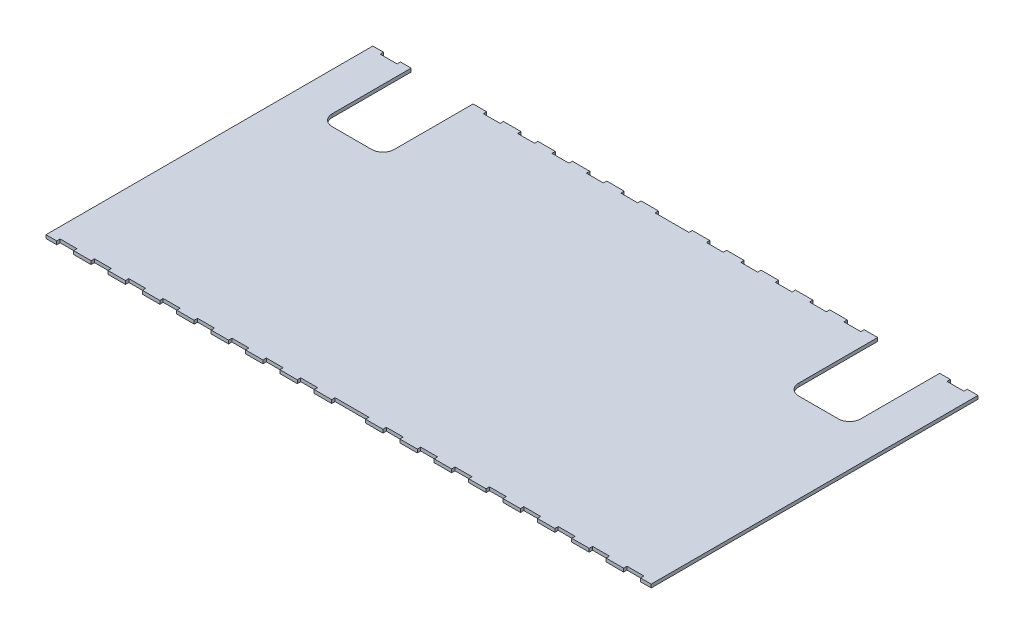
SolidWorks part; units mm, degrees
ref_plane "Front Plane" through (0, 0, 0) normal (0, 0, 1) x (1, 0, 0)
ref_plane "Top Plane" through (0, 0, 0) normal (0, 1, 0) x (1, 0, 0)
ref_plane "Right Plane" through (0, 0, 0) normal (1, 0, 0) x (0, 0, -1)
sketch "Sketch1" plane through (0, 0, 0) normal (0, 1, 0) x (1, 0, 0)
  line L1 (-268.5, 145) -> (268.5, 145)
  line L2 (-268.5, 145) -> (-268.5, -145)
  line L3 (-268.5, -145) -> (268.5, -145)
  line L4 (268.5, 145) -> (268.5, -145)
  line L5 (-268.5, 145) -> (268.5, -145) construction
  line L6 (-268.5, -145) -> (268.5, 145) construction
  line L7 (234.5, 145) -> (179.5, 145)
  line L8 (234.5, 145) -> (234.5, 65)
  line L9 (234.5, 65) -> (179.5, 65)
  line L10 (179.5, 145) -> (179.5, 65)
  line L15 (0, 145) -> (0, -145) construction
  line L16 (-179.5, 145) -> (-179.5, 65)
  line L17 (-234.5, 65) -> (-179.5, 65)
  line L18 (-234.5, 145) -> (-234.5, 65)
  line L19 (-234.5, 145) -> (-179.5, 145)
  point P0 (0, 0)
  dimension "D1" = 537
  dimension "D2" = 290
  dimension "D3" = 34
  dimension "D4" = 80
  dimension "D5" = 55
extrude "Boss-Extrude1" add sketch "Sketch1" along normal blind 3 contours L18 L1 L2 L3 L4 L8 L9 L10 L16 L17
fillet "Fillet1" radius 10 4 edges at (179.5, 1.5, -65) (234.5, 1.5, -65) (-179.5, 1.5, -65) (-234.5, 1.5, -65)
sketch "Sketch2" plane through (0, 3, 0) normal (0, 1, 0) x (1, 0, 0)
  line L1 (-259, 145) -> (-244, 145)
  line L2 (-259, 145) -> (-259, 142)
  line L3 (-259, 142) -> (-244, 142)
  line L4 (-244, 145) -> (-244, 142)
  line L5 (-259, 143.5) -> (-268.5, 143.5) construction
  line L6 (-268.5, 145) -> (-268.5, -145) construction
  line L7 (-244, 143.5) -> (-234.5, 143.5) construction
  line L9 (-228.5, 145) -> (-213.5, 145)
  line L14 (0, 145) -> (0, -145) construction
  line L15 (-179.5, 145) -> (179.5, 145) construction
  line L16 (-268.5, -145) -> (268.5, -145) construction
  line L21 (-228.5, 145) -> (-228.5, 142)
  line L22 (-228.5, 142) -> (-213.5, 142)
  line L27 (-213.5, 145) -> (-213.5, 142)
  line L28 (-198, 145) -> (-183, 145)
  line L33 (-198, 145) -> (-198, 142)
  line L34 (-198, 142) -> (-183, 142)
  line L39 (-183, 145) -> (-183, 142)
  line L40 (-167.5, 145) -> (-152.5, 145)
  line L45 (-167.5, 145) -> (-167.5, 142)
  line L46 (-167.5, 142) -> (-152.5, 142)
  line L51 (-152.5, 145) -> (-152.5, 142)
  line L52 (-137, 145) -> (-122, 145)
  line L53 (-137, 145) -> (-137, 142)
  line L54 (-137, 142) -> (-122, 142)
  line L55 (-122, 145) -> (-122, 142)
  line L56 (-106.5, 145) -> (-91.5, 145)
  line L57 (-106.5, 145) -> (-106.5, 142)
  line L58 (-106.5, 142) -> (-91.5, 142)
  line L59 (-91.5, 145) -> (-91.5, 142)
  line L60 (-76, 145) -> (-61, 145)
  line L61 (-76, 145) -> (-76, 142)
  line L62 (-76, 142) -> (-61, 142)
  line L63 (-61, 145) -> (-61, 142)
  line L64 (-45.5, 145) -> (-30.5, 145)
  line L65 (-45.5, 145) -> (-45.5, 142)
  line L94 (-268.5, 0) -> (268.5, 0) construction
  line L95 (268.5, 145) -> (268.5, -145) construction
  line L96 (-45.5, 142) -> (-30.5, 142)
  line L97 (-30.5, 145) -> (-30.5, 142)
  line L98 (-15, 145) -> (0, 145)
  line L99 (-15, 145) -> (-15, 142)
  line L100 (-15, 142) -> (15, 142)
  line L101 (0, 145) -> (0, 142)
  line L102 (-268.5, 145) -> (-234.5, 145) construction
  line L103 (-234.5, 145) -> (-234.5, 75) construction
  line L104 (244, 143.5) -> (234.5, 143.5) construction
  line L105 (259, 143.5) -> (268.5, 143.5) construction
  line L106 (15, 145) -> (15, 142)
  line L107 (15, 145) -> (0, 145)
  line L108 (30.5, 145) -> (30.5, 142)
  line L109 (45.5, 142) -> (30.5, 142)
  line L110 (45.5, 145) -> (45.5, 142)
  line L111 (45.5, 145) -> (30.5, 145)
  line L112 (61, 145) -> (61, 142)
  line L113 (76, 142) -> (61, 142)
  line L114 (76, 145) -> (76, 142)
  line L115 (76, 145) -> (61, 145)
  line L116 (91.5, 145) -> (91.5, 142)
  line L117 (106.5, 142) -> (91.5, 142)
  line L118 (106.5, 145) -> (106.5, 142)
  line L119 (106.5, 145) -> (91.5, 145)
  line L120 (122, 145) -> (122, 142)
  line L121 (137, 142) -> (122, 142)
  line L122 (137, 145) -> (137, 142)
  line L123 (137, 145) -> (122, 145)
  line L124 (152.5, 145) -> (152.5, 142)
  line L125 (167.5, 142) -> (152.5, 142)
  line L126 (167.5, 145) -> (167.5, 142)
  line L127 (167.5, 145) -> (152.5, 145)
  line L128 (183, 145) -> (183, 142)
  line L129 (198, 142) -> (183, 142)
  line L130 (198, 145) -> (198, 142)
  line L131 (198, 145) -> (183, 145)
  line L132 (213.5, 145) -> (213.5, 142)
  line L133 (228.5, 142) -> (213.5, 142)
  line L134 (228.5, 145) -> (228.5, 142)
  line L135 (228.5, 145) -> (213.5, 145)
  line L136 (244, 145) -> (244, 142)
  line L137 (259, 142) -> (244, 142)
  line L138 (259, 145) -> (259, 142)
  line L139 (259, 145) -> (244, 145)
  line L140 (259, -143.5) -> (268.5, -143.5) construction
  line L141 (244, -143.5) -> (234.5, -143.5) construction
  line L142 (-244, -143.5) -> (-234.5, -143.5) construction
  line L143 (-259, -143.5) -> (-268.5, -143.5) construction
  line L144 (259, -145) -> (244, -145)
  line L145 (259, -145) -> (259, -142)
  line L146 (259, -142) -> (244, -142)
  line L147 (244, -145) -> (244, -142)
  line L148 (228.5, -145) -> (213.5, -145)
  line L149 (228.5, -145) -> (228.5, -142)
  line L150 (228.5, -142) -> (213.5, -142)
  line L151 (213.5, -145) -> (213.5, -142)
  line L152 (198, -145) -> (183, -145)
  line L153 (198, -145) -> (198, -142)
  line L154 (198, -142) -> (183, -142)
  line L155 (183, -145) -> (183, -142)
  line L156 (167.5, -145) -> (152.5, -145)
  line L157 (167.5, -145) -> (167.5, -142)
  line L158 (167.5, -142) -> (152.5, -142)
  line L159 (152.5, -145) -> (152.5, -142)
  line L160 (137, -145) -> (122, -145)
  line L161 (137, -145) -> (137, -142)
  line L162 (137, -142) -> (122, -142)
  line L163 (122, -145) -> (122, -142)
  line L164 (106.5, -145) -> (91.5, -145)
  line L165 (106.5, -145) -> (106.5, -142)
  line L166 (106.5, -142) -> (91.5, -142)
  line L167 (91.5, -145) -> (91.5, -142)
  line L168 (76, -145) -> (61, -145)
  line L169 (76, -145) -> (76, -142)
  line L170 (76, -142) -> (61, -142)
  line L171 (61, -145) -> (61, -142)
  line L172 (45.5, -145) -> (30.5, -145)
  line L173 (45.5, -145) -> (45.5, -142)
  line L174 (45.5, -142) -> (30.5, -142)
  line L175 (30.5, -145) -> (30.5, -142)
  line L176 (15, -145) -> (0, -145)
  line L177 (15, -145) -> (15, -142)
  line L178 (0, -145) -> (0, -142)
  line L179 (-15, -142) -> (15, -142)
  line L180 (-15, -145) -> (-15, -142)
  line L181 (-15, -145) -> (0, -145)
  line L182 (-30.5, -145) -> (-30.5, -142)
  line L183 (-45.5, -142) -> (-30.5, -142)
  line L184 (-45.5, -145) -> (-45.5, -142)
  line L185 (-45.5, -145) -> (-30.5, -145)
  line L186 (-61, -145) -> (-61, -142)
  line L187 (-76, -142) -> (-61, -142)
  line L188 (-76, -145) -> (-76, -142)
  line L189 (-76, -145) -> (-61, -145)
  line L190 (-91.5, -145) -> (-91.5, -142)
  line L191 (-106.5, -142) -> (-91.5, -142)
  line L192 (-106.5, -145) -> (-106.5, -142)
  line L193 (-106.5, -145) -> (-91.5, -145)
  line L194 (-122, -145) -> (-122, -142)
  line L195 (-137, -142) -> (-122, -142)
  line L196 (-137, -145) -> (-137, -142)
  line L197 (-137, -145) -> (-122, -145)
  line L198 (-152.5, -145) -> (-152.5, -142)
  line L199 (-167.5, -142) -> (-152.5, -142)
  line L200 (-167.5, -145) -> (-167.5, -142)
  line L201 (-167.5, -145) -> (-152.5, -145)
  line L202 (-183, -145) -> (-183, -142)
  line L203 (-198, -142) -> (-183, -142)
  line L204 (-198, -145) -> (-198, -142)
  line L205 (-198, -145) -> (-183, -145)
  line L206 (-213.5, -145) -> (-213.5, -142)
  line L207 (-228.5, -142) -> (-213.5, -142)
  line L208 (-228.5, -145) -> (-228.5, -142)
  line L209 (-228.5, -145) -> (-213.5, -145)
  line L210 (-244, -145) -> (-244, -142)
  line L211 (-259, -142) -> (-244, -142)
  line L212 (-259, -145) -> (-259, -142)
  line L213 (-259, -145) -> (-244, -145)
  point P13 (-259, 145)
  point P14 (-268.5, 143.5048)
  point P20 (0, 142)
  point P21 (-259, 143.5)
  point P54 (-244, 143.5)
  point P55 (-234.5, 143.5)
  point P58 (-234.5, 143.6543)
  point P59 (-259.8475, 145)
  line M50 (-234.5, 145) -> (-268.5, 145)
  line M52 (-268.5, -145) -> (268.5, -145)
  line M54 (268.5, 145) -> (234.5, 145)
  line M60 (179.5, 145) -> (-179.5, 145)
extrude "Cut-Extrude2" cut sketch "Sketch2" against normal through all contours L4 L2 L3 M50 | L27 L9 L21 L22 | L39 L28 L33 L34 | L51 L45 L46 M60 | L55 L53 L54 M60 | L59 L57 L58 M60 | L63 L61 L62 M60 | L97 L65 L96 M60 | L101 L99 L100 M60 | L106 L101 L100 M60 | L110 L108 L109 M60 | L114 L112 L113 M60 | L118 L116 L117 M60 | L122 L120 L121 M60 | L126 L124 L125 M60 | L130 L131 L128 L129 | L134 L135 L132 L133 | L138 L136 L137 M54 | L212 L210 L211 M52 | L208 L206 L207 M52 | L204 L202 L203 M52 | L200 L198 L199 M52 | L196 L194 L195 M52 | L192 L190 L191 M52 | L188 L186 L187 M52 | L184 L182 L183 M52 | L180 L178 L179 M52 | L179 L178 L177 M52 | L175 L173 L174 M52 | L171 L169 L170 M52 | L167 L165 L166 M52 | L163 L161 L162 M52 | L159 L157 L158 M52 | L155 L153 L154 M52 | L151 L149 L150 M52 | L147 L145 L146 M52
